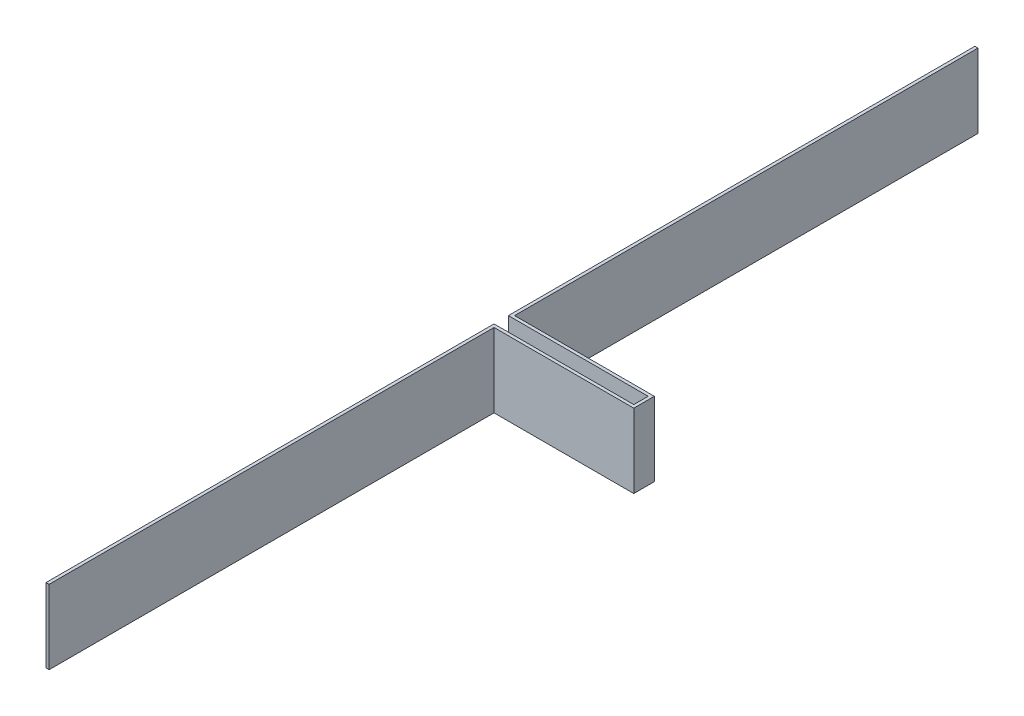
SolidWorks part; units mm, degrees
material "Pine"
ref_plane "Front Plane" through (0, 0, 0) normal (0, 0, 1) x (1, 0, 0)
ref_plane "Top Plane" through (0, 0, 0) normal (0, 1, 0) x (1, 0, 0)
ref_plane "Right Plane" through (0, 0, 0) normal (1, 0, 0) x (0, 0, -1)
sketch "Sketch1" plane through (0, 0, 0) normal (0, 1, 0) x (1, 0, 0)
  line L0 (0, 0) -> (0, 2768.6)
  line L1 (0, 2768.6) -> (863.6, 2768.6)
  line L2 (863.6, 2768.6) -> (863.6, 2857.5)
  line L3 (863.6, 2857.5) -> (0, 2857.5)
  line L4 (0, 2857.5) -> (0, 5740.4)
  line L5 (0, 5740.4) -> (19.05, 5740.4)
  line L6 (19.05, 5740.4) -> (19.05, 2876.55)
  line L7 (19.05, 2876.55) -> (882.65, 2876.55)
  line L8 (882.65, 2876.55) -> (882.65, 2749.55)
  line L9 (882.65, 2749.55) -> (19.05, 2749.55)
  line L10 (19.05, 2749.55) -> (19.05, 0)
  line L11 (19.05, 0) -> (0, 0)
  line L12 (834.9745, 2876.55) -> (834.9745, 2857.5) construction
  line L13 (244.24, 2768.6) -> (244.24, 2749.55) construction
  line L14 (863.6, 2818.8798) -> (882.65, 2818.8798) construction
  dimension "D1" = 19.05
  dimension "D2" = 88.9
  dimension "D3" = 863.6
  dimension "D4" = 2882.9
  dimension "D5" = 2768.6
extrude "Boss-Extrude1" add sketch "Sketch1" along normal blind 457.2
